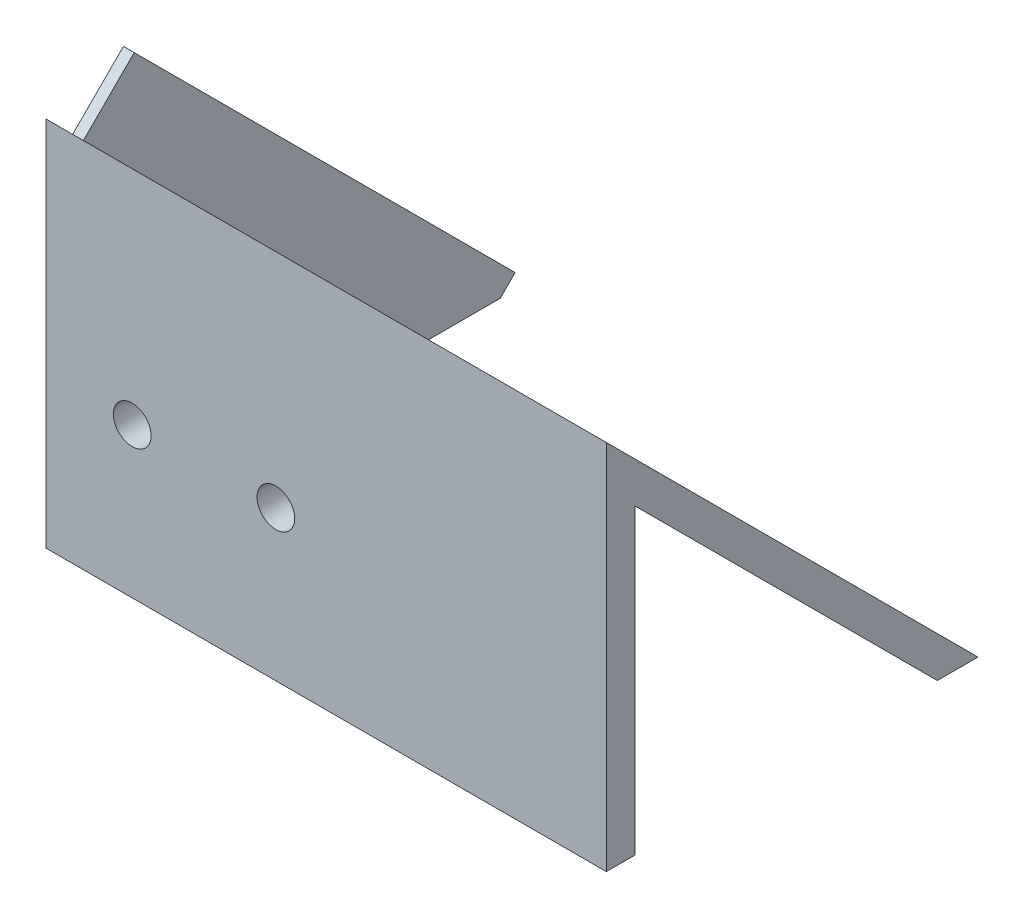
SolidWorks part; units mm, degrees
ref_plane "Front Plane" through (0, 0, 0) normal (0, 0, 1) x (1, 0, 0)
ref_plane "Top Plane" through (0, 0, 0) normal (0, 1, 0) x (1, 0, 0)
ref_plane "Right Plane" through (0, 0, 0) normal (1, 0, 0) x (0, 0, -1)
sketch "Sketch1" plane through (0, 0, 0) normal (1, 0, 0) x (0, 0, -1)
  line L0 (0, 0) -> (0, 56.74)
  line L1 (0, 56.74) -> (56.74, 0)
  line L2 (56.74, 0) -> (51.08, 0)
  line L3 (4, 0) -> (4, 47.08)
  line L4 (4, 47.08) -> (51.08, 0)
  line L5 (4, 0) -> (0, 0)
  dimension "D1" = 56.74
  dimension "D2" = 45
  dimension "D3" = 4
  dimension "D4" = 45
  dimension "D5" = 47.08
  dimension "D6" = 4.0022
extrude "Boss-Extrude1" add sketch "Sketch1" along normal blind 78
sketch "Sketch2" plane through (0, 28.37, -28.37) normal (0, 0.7071, -0.7071) x (1, 0, 0)
  line L5 (0, 40.1212) -> (1.5, 40.1212)
  line L6 (0, 40.1212) -> (0, -34.8788)
  line L7 (0, -34.8788) -> (1.5, -34.8788)
  line L8 (1.5, 40.1212) -> (1.5, -34.8788)
  dimension "D3" = 75
  dimension "D4" = 1.5
extrude "Boss-Extrude2" add sketch "Sketch2" along normal blind 10
sketch "Sketch4" plane through (0, 0, 0) normal (0, 0, 1) x (1, 0, 0)
  line L0 (0, 56.74) -> (0, 0) construction
  line L2 (78, 56.74) -> (0, 56.74) construction
  circle A0 centre (12, 25.86) radius 2.625
  circle A1 centre (32, 25.86) radius 2.625
  dimension "D1" = 5.25
  dimension "D2" = 12
  dimension "D3" = 30.88
  dimension "D4" = 5.25
  dimension "D5" = 30.88
  dimension "D6" = 20
extrude "Cut-Extrude1" cut sketch "Sketch4" against normal up to next
sketch "Sketch5" plane through (0, 0, 0) normal (0, 0, 1) x (1, 0, 0)
  line L0 (78, 56.74) -> (78, 0) construction
  line L1 (0, 0) -> (78, 0)
  line L2 (0, 0) -> (0, 5)
  line L3 (0, 5) -> (78, 5)
  line L4 (78, 0) -> (78, 5)
  dimension "D1" = 5
extrude "Cut-Extrude2" cut sketch "Sketch5" against normal through all
